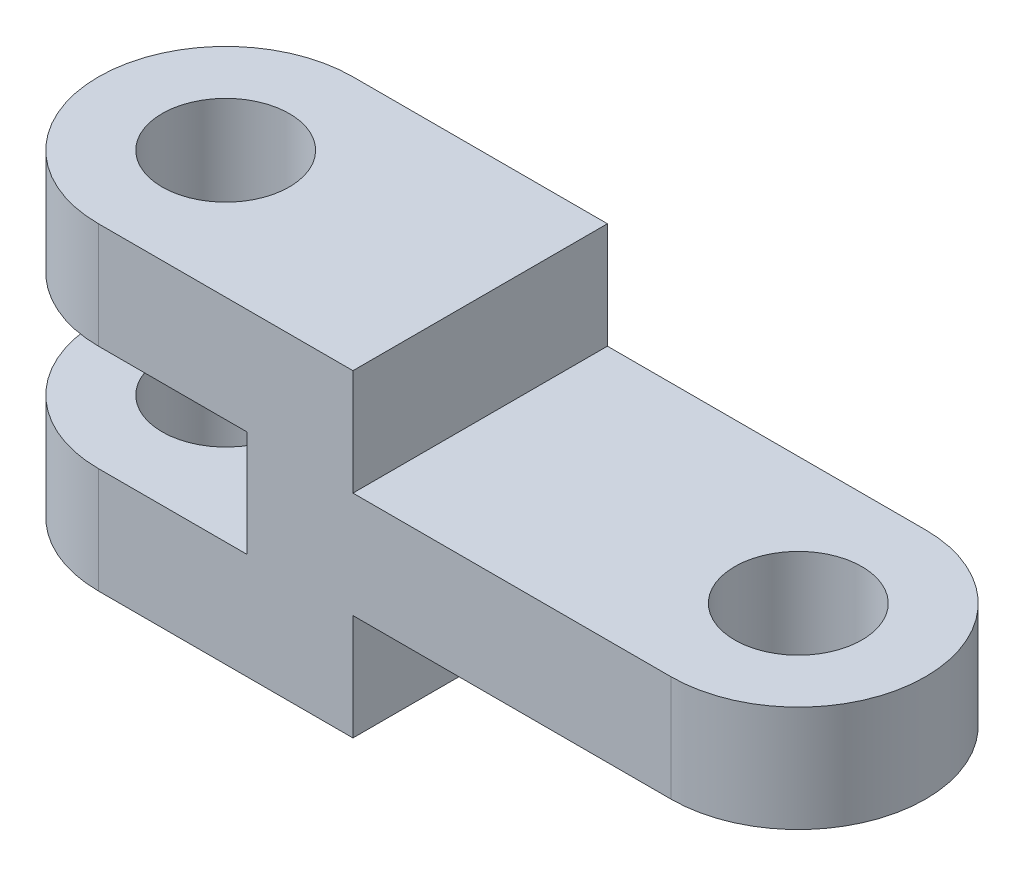
SolidWorks part; units mm, degrees
ref_plane "Front Plane" through (0, 0, 0) normal (0, 0, 1) x (1, 0, 0)
ref_plane "Top Plane" through (0, 0, 0) normal (0, 1, 0) x (1, 0, 0)
ref_plane "Right Plane" through (0, 0, 0) normal (1, 0, 0) x (0, 0, -1)
sketch "Sketch1" plane through (0, 0, 0) normal (0, 0, 1) x (1, 0, 0)
  line L0 (0, 0) -> (60, 0)
  line L1 (60, 0) -> (60, -25)
  line L2 (60, -25) -> (135, -25)
  line L3 (135, -25) -> (135, -50)
  line L4 (135, -50) -> (60, -50)
  line L5 (60, -50) -> (60, -75)
  line L6 (60, -75) -> (0, -75)
  line L7 (0, -75) -> (0, -50)
  line L8 (0, -50) -> (35, -50)
  line L9 (35, -50) -> (35, -25)
  line L10 (35, -25) -> (0, -25)
  line L11 (0, -25) -> (0, 0)
  dimension "D1" = 75
  dimension "D2" = 135
  dimension "D3" = 25
  dimension "D4" = 25
  dimension "D5" = 25
  dimension "D6" = 35
extrude "Boss-Extrude1" add sketch "Sketch1" along normal blind 60
sketch "Sketch3" plane through (0, 0, 0) normal (0, 1, 0) x (1, 0, 0)
  line L0 (60, -60) -> (0, -60) construction
  line L1 (0, -60) -> (0, 0) construction
  line L2 (0, 0) -> (0, -60)
  arc A0 (0, 0) -> (0, -60) centre (0, -30) ccw
  dimension "D1" = 30
extrude "Boss-Extrude2" add sketch "Sketch3" against normal blind 25
sketch "Sketch4" plane through (0, -50, 0) normal (0, 1, 0) x (1, 0, 0)
  line L4 (35, 0) -> (0, 0)
  line L5 (0, 0) -> (0, -60)
  line L6 (0, -60) -> (35, -60)
  line L7 (35, -60) -> (35, 0)
  line L9 (0, 0) -> (0, -60)
  arc A0 (0, 0) -> (0, -60) centre (0, -30) ccw
  dimension "D1" = 30
  dimension "D2" = 0
extrude "Boss-Extrude3" add sketch "Sketch4" against normal blind 25
sketch "Sketch5" plane through (0, -25, 0) normal (0, 1, 0) x (1, 0, 0)
  line L0 (135, 0) -> (135, -60)
  arc A0 (135, 0) -> (135, -60) centre (135, -30) cw
  dimension "D1" = 30
extrude "Boss-Extrude4" add sketch "Sketch5" against normal blind 25
sketch "Sketch6" plane through (0, 0, 0) normal (0, 1, 0) x (1, 0, 0)
  circle A0 centre (0, -30) radius 15
  arc A3 (0, 0) -> (0, -60) centre (0, -30) ccw construction
  point P6 (0, 0)
  point P7 (0, 0)
  dimension "D1" = 30
extrude "Cut-Extrude2" cut sketch "Sketch6" against normal through all both
sketch "Sketch7" plane through (0, -25, 0) normal (0, 1, 0) x (1, 0, 0)
  circle A0 centre (135, -30) radius 15
  dimension "D1" = 30
extrude "Cut-Extrude3" cut sketch "Sketch7" against normal through all both
sketch "Sketch8" plane through (0, 0, 60) normal (0, 0, 1) x (1, 0, 0)
  text T0 "ABHAY CIVIL D1 25BCL048"
  point P1 (0, 0)
